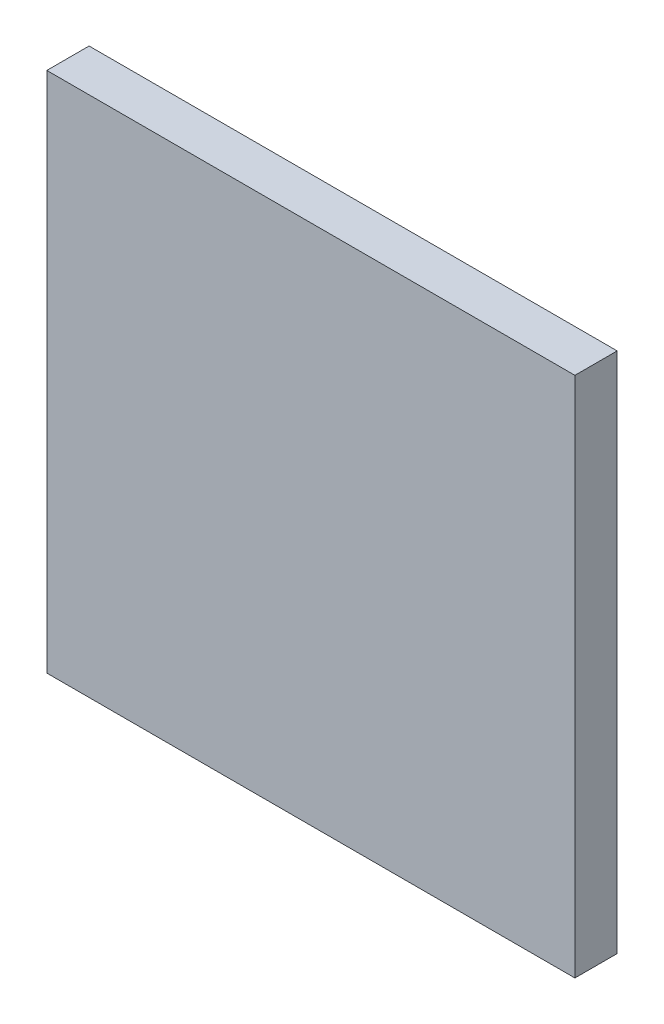
SolidWorks part; units mm, degrees
ref_plane "Front Plane" through (0, 0, 0) normal (0, 0, 1) x (1, 0, 0)
ref_plane "Top Plane" through (0, 0, 0) normal (0, 1, 0) x (1, 0, 0)
ref_plane "Right Plane" through (0, 0, 0) normal (1, 0, 0) x (0, 0, -1)
sketch "Sketch1" plane through (0, 0, 0) normal (0, 0, 1) x (1, 0, 0)
  line L0 (-6.245, 6.5997) -> (6.245, 6.5997)
  line L1 (6.245, 6.5997) -> (6.245, -5.745)
  line L2 (6.245, -5.745) -> (-6.245, -5.745)
  line L3 (-6.245, -5.745) -> (-6.245, 6.5997)
extrude "Component_Outline" add sketch "Sketch1" along normal blind 1 separate body
sketch3d "3DSketch1"
  line L0 (0, 0, 0) -> (1, 0, 0)
  line L1 (0, 0, 0) -> (0, 1, 0)
  line L2 (0, 0, 0) -> (0, 0, 1)
  point P0 (0, 0, 0)
